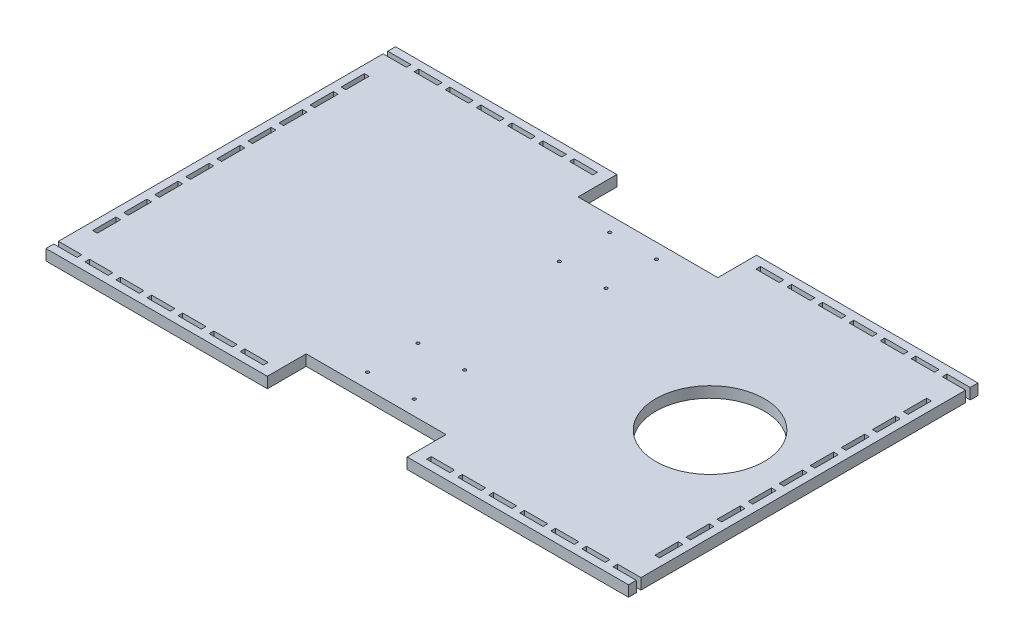
SolidWorks part; units mm, degrees
material "Thornel Mat VMA"
ref_plane "Front Plane" through (0, 0, 0) normal (0, 0, 1) x (1, 0, 0)
ref_plane "Top Plane" through (0, 0, 0) normal (0, 1, 0) x (1, 0, 0)
ref_plane "Right Plane" through (0, 0, 0) normal (1, 0, 0) x (0, 0, -1)
sketch "Sketch6" plane through (0, 0, 0) normal (0, 1, 0) x (1, 0, 0)
  line L0 (-187.5, 0) -> (187.5, 0) construction
  line L1 (-187.5, 112.5) -> (187.5, 112.5)
  line L2 (-187.5, 112.5) -> (-187.5, -112.5)
  line L3 (-187.5, -112.5) -> (187.5, -112.5)
  line L4 (187.5, 112.5) -> (187.5, -112.5)
  line L5 (0, -112.5) -> (0, -87.5) construction
  line L7 (187.5, -107.5) -> (172.5, -107.5)
  line L8 (187.5, -107.5) -> (187.5, -104.5)
  line L9 (187.5, -104.5) -> (172.5, -104.5)
  line L10 (172.5, -107.5) -> (172.5, -104.5)
  line L35 (187.5, 107.5) -> (172.5, 107.5)
  line L36 (187.5, 107.5) -> (187.5, 104.5)
  line L37 (187.5, 104.5) -> (172.5, 104.5)
  line L38 (172.5, 107.5) -> (172.5, 104.5)
  line L63 (-187.5, 104.5) -> (-172.5, 104.5)
  line L64 (-187.5, 104.5) -> (-187.5, 107.5)
  line L65 (-187.5, 107.5) -> (-172.5, 107.5)
  line L66 (-172.5, 104.5) -> (-172.5, 107.5)
  line L91 (-187.5, -107.5) -> (-172.5, -107.5)
  line L92 (-187.5, -107.5) -> (-187.5, -104.5)
  line L93 (-187.5, -104.5) -> (-172.5, -104.5)
  line L94 (-172.5, -107.5) -> (-172.5, -104.5)
  line L118 (167.5, 107.5) -> (152.5, 107.5)
  line L119 (152.5, 107.5) -> (152.5, 104.5)
  line L120 (167.5, 104.5) -> (152.5, 104.5)
  line L121 (167.5, 107.5) -> (167.5, 104.5)
  line L122 (167.5, -107.5) -> (152.5, -107.5)
  line L123 (152.5, -107.5) -> (152.5, -104.5)
  line L124 (167.5, -104.5) -> (152.5, -104.5)
  line L125 (167.5, -107.5) -> (167.5, -104.5)
  line L126 (147.5, 107.5) -> (132.5, 107.5)
  line L127 (132.5, 107.5) -> (132.5, 104.5)
  line L128 (147.5, 104.5) -> (132.5, 104.5)
  line L129 (147.5, 107.5) -> (147.5, 104.5)
  line L130 (147.5, -107.5) -> (132.5, -107.5)
  line L131 (132.5, -107.5) -> (132.5, -104.5)
  line L132 (147.5, -104.5) -> (132.5, -104.5)
  line L133 (147.5, -107.5) -> (147.5, -104.5)
  line L134 (127.5, 107.5) -> (112.5, 107.5)
  line L135 (112.5, 107.5) -> (112.5, 104.5)
  line L136 (127.5, 104.5) -> (112.5, 104.5)
  line L137 (127.5, 107.5) -> (127.5, 104.5)
  line L138 (127.5, -107.5) -> (112.5, -107.5)
  line L139 (112.5, -107.5) -> (112.5, -104.5)
  line L140 (127.5, -104.5) -> (112.5, -104.5)
  line L141 (127.5, -107.5) -> (127.5, -104.5)
  line L142 (107.5, 107.5) -> (92.5, 107.5)
  line L143 (92.5, 107.5) -> (92.5, 104.5)
  line L144 (107.5, 104.5) -> (92.5, 104.5)
  line L145 (107.5, 107.5) -> (107.5, 104.5)
  line L146 (107.5, -107.5) -> (92.5, -107.5)
  line L147 (92.5, -107.5) -> (92.5, -104.5)
  line L148 (107.5, -104.5) -> (92.5, -104.5)
  line L149 (107.5, -107.5) -> (107.5, -104.5)
  line L150 (87.5, 107.5) -> (72.5, 107.5)
  line L151 (72.5, 107.5) -> (72.5, 104.5)
  line L152 (87.5, 104.5) -> (72.5, 104.5)
  line L153 (87.5, 107.5) -> (87.5, 104.5)
  line L154 (87.5, -107.5) -> (72.5, -107.5)
  line L155 (72.5, -107.5) -> (72.5, -104.5)
  line L156 (87.5, -104.5) -> (72.5, -104.5)
  line L157 (87.5, -107.5) -> (87.5, -104.5)
  line L158 (67.5, 107.5) -> (52.5, 107.5)
  line L159 (52.5, 107.5) -> (52.5, 104.5)
  line L160 (67.5, 104.5) -> (52.5, 104.5)
  line L161 (67.5, 107.5) -> (67.5, 104.5)
  line L162 (67.5, -107.5) -> (52.5, -107.5)
  line L163 (52.5, -107.5) -> (52.5, -104.5)
  line L164 (67.5, -104.5) -> (52.5, -104.5)
  line L165 (67.5, -107.5) -> (67.5, -104.5)
  line L166 (-167.5, -107.5) -> (-152.5, -107.5)
  line L167 (-152.5, -107.5) -> (-152.5, -104.5)
  line L168 (-167.5, -104.5) -> (-152.5, -104.5)
  line L169 (-167.5, -107.5) -> (-167.5, -104.5)
  line L170 (-167.5, 104.5) -> (-152.5, 104.5)
  line L171 (-152.5, 104.5) -> (-152.5, 107.5)
  line L172 (-167.5, 107.5) -> (-152.5, 107.5)
  line L173 (-167.5, 104.5) -> (-167.5, 107.5)
  line L174 (-147.5, -107.5) -> (-132.5, -107.5)
  line L175 (-132.5, -107.5) -> (-132.5, -104.5)
  line L176 (-147.5, -104.5) -> (-132.5, -104.5)
  line L177 (-147.5, -107.5) -> (-147.5, -104.5)
  line L178 (-147.5, 104.5) -> (-132.5, 104.5)
  line L179 (-132.5, 104.5) -> (-132.5, 107.5)
  line L180 (-147.5, 107.5) -> (-132.5, 107.5)
  line L181 (-147.5, 104.5) -> (-147.5, 107.5)
  line L182 (-127.5, -107.5) -> (-112.5, -107.5)
  line L183 (-112.5, -107.5) -> (-112.5, -104.5)
  line L184 (-127.5, -104.5) -> (-112.5, -104.5)
  line L185 (-127.5, -107.5) -> (-127.5, -104.5)
  line L186 (-127.5, 104.5) -> (-112.5, 104.5)
  line L187 (-112.5, 104.5) -> (-112.5, 107.5)
  line L188 (-127.5, 107.5) -> (-112.5, 107.5)
  line L189 (-127.5, 104.5) -> (-127.5, 107.5)
  line L190 (-107.5, -107.5) -> (-92.5, -107.5)
  line L191 (-92.5, -107.5) -> (-92.5, -104.5)
  line L192 (-107.5, -104.5) -> (-92.5, -104.5)
  line L193 (-107.5, -107.5) -> (-107.5, -104.5)
  line L194 (-107.5, 104.5) -> (-92.5, 104.5)
  line L195 (-92.5, 104.5) -> (-92.5, 107.5)
  line L196 (-107.5, 107.5) -> (-92.5, 107.5)
  line L197 (-107.5, 104.5) -> (-107.5, 107.5)
  line L198 (-87.5, -107.5) -> (-72.5, -107.5)
  line L199 (-72.5, -107.5) -> (-72.5, -104.5)
  line L200 (-87.5, -104.5) -> (-72.5, -104.5)
  line L201 (-87.5, -107.5) -> (-87.5, -104.5)
  line L202 (-87.5, 104.5) -> (-72.5, 104.5)
  line L203 (-72.5, 104.5) -> (-72.5, 107.5)
  line L204 (-87.5, 107.5) -> (-72.5, 107.5)
  line L205 (-87.5, 104.5) -> (-87.5, 107.5)
  line L206 (-67.5, -107.5) -> (-52.5, -107.5)
  line L207 (-52.5, -107.5) -> (-52.5, -104.5)
  line L208 (-67.5, -104.5) -> (-52.5, -104.5)
  line L209 (-67.5, -107.5) -> (-67.5, -104.5)
  line L210 (-67.5, 104.5) -> (-52.5, 104.5)
  line L211 (-52.5, 104.5) -> (-52.5, 107.5)
  line L212 (-67.5, 107.5) -> (-52.5, 107.5)
  line L213 (-67.5, 104.5) -> (-67.5, 107.5)
  line L214 (0, -112.5) -> (0, -87.5) construction
  line L215 (45, -112.5) -> (-45, -112.5)
  line L216 (45, -112.5) -> (45, -87.5)
  line L217 (45, -87.5) -> (-45, -87.5)
  line L218 (-45, -112.5) -> (-45, -87.5)
  line L219 (45, 87.5) -> (-45, 87.5)
  line L220 (45, -100) -> (-45, -100) construction
  line L221 (-45, 112.5) -> (-45, 87.5)
  line L222 (45, 112.5) -> (-45, 112.5)
  line L223 (45, 112.5) -> (45, 87.5)
  line L224 (179.5, 0) -> (182.5, 0) construction
  line L225 (182.5, -7.5) -> (179.5, -7.5)
  line L226 (182.5, -7.5) -> (182.5, 7.5)
  line L227 (182.5, 7.5) -> (179.5, 7.5)
  line L228 (179.5, -7.5) -> (179.5, 7.5)
  line L229 (187.5, 0) -> (182.5, 0) construction
  line L230 (181, -7.5) -> (181, 7.5) construction
  line L231 (182.5, 12.5) -> (182.5, 27.5)
  line L232 (182.5, 12.5) -> (179.5, 12.5)
  line L233 (179.5, 12.5) -> (179.5, 27.5)
  line L234 (182.5, 27.5) -> (179.5, 27.5)
  line L235 (182.5, 32.5) -> (182.5, 47.5)
  line L236 (182.5, 32.5) -> (179.5, 32.5)
  line L237 (179.5, 32.5) -> (179.5, 47.5)
  line L238 (182.5, 47.5) -> (179.5, 47.5)
  line L239 (182.5, 52.5) -> (182.5, 67.5)
  line L240 (182.5, 52.5) -> (179.5, 52.5)
  line L241 (179.5, 52.5) -> (179.5, 67.5)
  line L242 (182.5, 67.5) -> (179.5, 67.5)
  line L243 (182.5, 72.5) -> (182.5, 87.5)
  line L244 (182.5, 72.5) -> (179.5, 72.5)
  line L245 (179.5, 72.5) -> (179.5, 87.5)
  line L246 (182.5, 87.5) -> (179.5, 87.5)
  line L247 (182.5, -7.5) -> (182.5, 7.5)
  line L248 (182.5, -7.5) -> (179.5, -7.5)
  line L249 (179.5, -7.5) -> (179.5, 7.5)
  line L250 (182.5, 7.5) -> (179.5, 7.5)
  line L251 (182.5, 12.5) -> (182.5, 27.5)
  line L252 (182.5, 12.5) -> (179.5, 12.5)
  line L253 (179.5, 12.5) -> (179.5, 27.5)
  line L254 (182.5, 27.5) -> (179.5, 27.5)
  line L255 (182.5, 32.5) -> (182.5, 47.5)
  line L256 (182.5, 32.5) -> (179.5, 32.5)
  line L257 (179.5, 32.5) -> (179.5, 47.5)
  line L258 (182.5, 47.5) -> (179.5, 47.5)
  line L259 (182.5, 52.5) -> (182.5, 67.5)
  line L260 (182.5, 52.5) -> (179.5, 52.5)
  line L261 (179.5, 52.5) -> (179.5, 67.5)
  line L262 (182.5, 67.5) -> (179.5, 67.5)
  line L263 (182.5, -27.5) -> (182.5, -12.5)
  line L264 (182.5, -27.5) -> (179.5, -27.5)
  line L265 (179.5, -27.5) -> (179.5, -12.5)
  line L266 (182.5, -12.5) -> (179.5, -12.5)
  line L267 (182.5, -7.5) -> (182.5, 7.5)
  line L268 (182.5, -7.5) -> (179.5, -7.5)
  line L269 (179.5, -7.5) -> (179.5, 7.5)
  line L270 (182.5, 7.5) -> (179.5, 7.5)
  line L271 (182.5, 12.5) -> (182.5, 27.5)
  line L272 (182.5, 12.5) -> (179.5, 12.5)
  line L273 (179.5, 12.5) -> (179.5, 27.5)
  line L274 (182.5, 27.5) -> (179.5, 27.5)
  line L275 (182.5, 32.5) -> (182.5, 47.5)
  line L276 (182.5, 32.5) -> (179.5, 32.5)
  line L277 (179.5, 32.5) -> (179.5, 47.5)
  line L278 (182.5, 47.5) -> (179.5, 47.5)
  line L279 (182.5, -47.5) -> (182.5, -32.5)
  line L280 (182.5, -47.5) -> (179.5, -47.5)
  line L281 (179.5, -47.5) -> (179.5, -32.5)
  line L282 (182.5, -32.5) -> (179.5, -32.5)
  line L283 (182.5, -27.5) -> (182.5, -12.5)
  line L284 (182.5, -27.5) -> (179.5, -27.5)
  line L285 (179.5, -27.5) -> (179.5, -12.5)
  line L286 (182.5, -12.5) -> (179.5, -12.5)
  line L287 (182.5, -7.5) -> (182.5, 7.5)
  line L288 (182.5, -7.5) -> (179.5, -7.5)
  line L289 (179.5, -7.5) -> (179.5, 7.5)
  line L290 (182.5, 7.5) -> (179.5, 7.5)
  line L291 (182.5, 12.5) -> (182.5, 27.5)
  line L292 (182.5, 12.5) -> (179.5, 12.5)
  line L293 (179.5, 12.5) -> (179.5, 27.5)
  line L294 (182.5, 27.5) -> (179.5, 27.5)
  line L295 (182.5, -67.5) -> (182.5, -52.5)
  line L296 (182.5, -67.5) -> (179.5, -67.5)
  line L297 (179.5, -67.5) -> (179.5, -52.5)
  line L298 (182.5, -52.5) -> (179.5, -52.5)
  line L299 (182.5, -47.5) -> (182.5, -32.5)
  line L300 (182.5, -47.5) -> (179.5, -47.5)
  line L301 (179.5, -47.5) -> (179.5, -32.5)
  line L302 (182.5, -32.5) -> (179.5, -32.5)
  line L303 (182.5, -27.5) -> (182.5, -12.5)
  line L304 (182.5, -27.5) -> (179.5, -27.5)
  line L305 (179.5, -27.5) -> (179.5, -12.5)
  line L306 (182.5, -12.5) -> (179.5, -12.5)
  line L307 (182.5, -7.5) -> (182.5, 7.5)
  line L308 (182.5, -7.5) -> (179.5, -7.5)
  line L309 (179.5, -7.5) -> (179.5, 7.5)
  line L310 (182.5, 7.5) -> (179.5, 7.5)
  line L311 (182.5, -27.5) -> (182.5, -12.5)
  line L312 (182.5, -27.5) -> (179.5, -27.5)
  line L313 (179.5, -27.5) -> (179.5, -12.5)
  line L314 (182.5, -12.5) -> (179.5, -12.5)
  line L315 (182.5, -47.5) -> (182.5, -32.5)
  line L316 (182.5, -47.5) -> (179.5, -47.5)
  line L317 (179.5, -47.5) -> (179.5, -32.5)
  line L318 (182.5, -32.5) -> (179.5, -32.5)
  line L319 (182.5, -67.5) -> (182.5, -52.5)
  line L320 (182.5, -67.5) -> (179.5, -67.5)
  line L321 (179.5, -67.5) -> (179.5, -52.5)
  line L322 (182.5, -52.5) -> (179.5, -52.5)
  line L323 (182.5, -87.5) -> (182.5, -72.5)
  line L324 (182.5, -87.5) -> (179.5, -87.5)
  line L325 (179.5, -87.5) -> (179.5, -72.5)
  line L326 (182.5, -72.5) -> (179.5, -72.5)
  line L327 (-179.5, 0) -> (-182.5, 0) construction
  line L328 (-179.5, 7.5) -> (-182.5, 7.5)
  line L329 (-179.5, 7.5) -> (-179.5, -7.5)
  line L330 (-179.5, -7.5) -> (-182.5, -7.5)
  line L331 (-182.5, 7.5) -> (-182.5, -7.5)
  line L332 (-187.5, 0) -> (-182.5, 0) construction
  line L333 (-181, 7.5) -> (-181, -7.5) construction
  line L334 (-179.5, 27.5) -> (-179.5, 12.5)
  line L335 (-179.5, 27.5) -> (-182.5, 27.5)
  line L336 (-182.5, 27.5) -> (-182.5, 12.5)
  line L337 (-179.5, 12.5) -> (-182.5, 12.5)
  line L338 (-179.5, 47.5) -> (-179.5, 32.5)
  line L339 (-179.5, 47.5) -> (-182.5, 47.5)
  line L340 (-182.5, 47.5) -> (-182.5, 32.5)
  line L341 (-179.5, 32.5) -> (-182.5, 32.5)
  line L342 (-179.5, 67.5) -> (-179.5, 52.5)
  line L343 (-179.5, 67.5) -> (-182.5, 67.5)
  line L344 (-182.5, 67.5) -> (-182.5, 52.5)
  line L345 (-179.5, 52.5) -> (-182.5, 52.5)
  line L346 (-179.5, 87.5) -> (-179.5, 72.5)
  line L347 (-179.5, 87.5) -> (-182.5, 87.5)
  line L348 (-182.5, 87.5) -> (-182.5, 72.5)
  line L349 (-179.5, 72.5) -> (-182.5, 72.5)
  line L350 (-179.5, 7.5) -> (-179.5, -7.5)
  line L351 (-179.5, 7.5) -> (-182.5, 7.5)
  line L352 (-182.5, 7.5) -> (-182.5, -7.5)
  line L353 (-179.5, -7.5) -> (-182.5, -7.5)
  line L354 (-179.5, 27.5) -> (-179.5, 12.5)
  line L355 (-179.5, 27.5) -> (-182.5, 27.5)
  line L356 (-182.5, 27.5) -> (-182.5, 12.5)
  line L357 (-179.5, 12.5) -> (-182.5, 12.5)
  line L358 (-179.5, 47.5) -> (-179.5, 32.5)
  line L359 (-179.5, 47.5) -> (-182.5, 47.5)
  line L360 (-182.5, 47.5) -> (-182.5, 32.5)
  line L361 (-179.5, 32.5) -> (-182.5, 32.5)
  line L362 (-179.5, 67.5) -> (-179.5, 52.5)
  line L363 (-179.5, 67.5) -> (-182.5, 67.5)
  line L364 (-182.5, 67.5) -> (-182.5, 52.5)
  line L365 (-179.5, 52.5) -> (-182.5, 52.5)
  line L366 (-179.5, -12.5) -> (-179.5, -27.5)
  line L367 (-179.5, -12.5) -> (-182.5, -12.5)
  line L368 (-182.5, -12.5) -> (-182.5, -27.5)
  line L369 (-179.5, -27.5) -> (-182.5, -27.5)
  line L370 (-179.5, 7.5) -> (-179.5, -7.5)
  line L371 (-179.5, 7.5) -> (-182.5, 7.5)
  line L372 (-182.5, 7.5) -> (-182.5, -7.5)
  line L373 (-179.5, -7.5) -> (-182.5, -7.5)
  line L374 (-179.5, 27.5) -> (-179.5, 12.5)
  line L375 (-179.5, 27.5) -> (-182.5, 27.5)
  line L376 (-182.5, 27.5) -> (-182.5, 12.5)
  line L377 (-179.5, 12.5) -> (-182.5, 12.5)
  line L378 (-179.5, 47.5) -> (-179.5, 32.5)
  line L379 (-179.5, 47.5) -> (-182.5, 47.5)
  line L380 (-182.5, 47.5) -> (-182.5, 32.5)
  line L381 (-179.5, 32.5) -> (-182.5, 32.5)
  line L382 (-179.5, -32.5) -> (-179.5, -47.5)
  line L383 (-179.5, -32.5) -> (-182.5, -32.5)
  line L384 (-182.5, -32.5) -> (-182.5, -47.5)
  line L385 (-179.5, -47.5) -> (-182.5, -47.5)
  line L386 (-179.5, -12.5) -> (-179.5, -27.5)
  line L387 (-179.5, -12.5) -> (-182.5, -12.5)
  line L388 (-182.5, -12.5) -> (-182.5, -27.5)
  line L389 (-179.5, -27.5) -> (-182.5, -27.5)
  line L390 (-179.5, 7.5) -> (-179.5, -7.5)
  line L391 (-179.5, 7.5) -> (-182.5, 7.5)
  line L392 (-182.5, 7.5) -> (-182.5, -7.5)
  line L393 (-179.5, -7.5) -> (-182.5, -7.5)
  line L394 (-179.5, 27.5) -> (-179.5, 12.5)
  line L395 (-179.5, 27.5) -> (-182.5, 27.5)
  line L396 (-182.5, 27.5) -> (-182.5, 12.5)
  line L397 (-179.5, 12.5) -> (-182.5, 12.5)
  line L398 (-179.5, -52.5) -> (-179.5, -67.5)
  line L399 (-179.5, -52.5) -> (-182.5, -52.5)
  line L400 (-182.5, -52.5) -> (-182.5, -67.5)
  line L401 (-179.5, -67.5) -> (-182.5, -67.5)
  line L402 (-179.5, -32.5) -> (-179.5, -47.5)
  line L403 (-179.5, -32.5) -> (-182.5, -32.5)
  line L404 (-182.5, -32.5) -> (-182.5, -47.5)
  line L405 (-179.5, -47.5) -> (-182.5, -47.5)
  line L406 (-179.5, -12.5) -> (-179.5, -27.5)
  line L407 (-179.5, -12.5) -> (-182.5, -12.5)
  line L408 (-182.5, -12.5) -> (-182.5, -27.5)
  line L409 (-179.5, -27.5) -> (-182.5, -27.5)
  line L410 (-179.5, 7.5) -> (-179.5, -7.5)
  line L411 (-179.5, 7.5) -> (-182.5, 7.5)
  line L412 (-182.5, 7.5) -> (-182.5, -7.5)
  line L413 (-179.5, -7.5) -> (-182.5, -7.5)
  line L414 (-179.5, -12.5) -> (-179.5, -27.5)
  line L415 (-179.5, -12.5) -> (-182.5, -12.5)
  line L416 (-182.5, -12.5) -> (-182.5, -27.5)
  line L417 (-179.5, -27.5) -> (-182.5, -27.5)
  line L418 (-179.5, -32.5) -> (-179.5, -47.5)
  line L419 (-179.5, -32.5) -> (-182.5, -32.5)
  line L420 (-182.5, -32.5) -> (-182.5, -47.5)
  line L421 (-179.5, -47.5) -> (-182.5, -47.5)
  line L422 (-179.5, -52.5) -> (-179.5, -67.5)
  line L423 (-179.5, -52.5) -> (-182.5, -52.5)
  line L424 (-182.5, -52.5) -> (-182.5, -67.5)
  line L425 (-179.5, -67.5) -> (-182.5, -67.5)
  line L426 (-179.5, -72.5) -> (-179.5, -87.5)
  line L427 (-179.5, -72.5) -> (-182.5, -72.5)
  line L428 (-182.5, -72.5) -> (-182.5, -87.5)
  line L429 (-179.5, -87.5) -> (-182.5, -87.5)
  line L430 (0, 0) -> (0, 112.5) construction
  line L432 (-15, -45.52) -> (15, -45.52) construction
  line L433 (45, 87.5) -> (45, 61.72) construction
  line L434 (45, 61.72) -> (15, 61.72) construction
  line L435 (15, -45.52) -> (15, -77.92) construction
  line L439 (15, -61.72) -> (45, -87.5) construction
  line L440 (45, -87.5) -> (45, -61.72) construction
  line L441 (45, -61.72) -> (15, -61.72) construction
  line L444 (-15, -45.52) -> (-16, -45.52) construction
  line L445 (15, 61.72) -> (15, 45.52) construction
  line L446 (15, 45.52) -> (-15, 45.52) construction
  line L448 (-15, -45.52) -> (-15, -77.92) construction
  line L449 (-15, -77.92) -> (-16, -77.92) construction
  line L450 (15, 77.92) -> (-15, 77.92) construction
  line L451 (-15, 77.92) -> (-15, 45.52) construction
  line L452 (-15, -77.92) -> (15, -77.92) construction
  line L453 (15, 77.92) -> (15, 61.72) construction
  line L454 (15, 61.72) -> (45, 87.5) construction
  circle A0 centre (127.5, 0) radius 35
  circle A1 centre (15, -45.52) radius 1
  circle A2 centre (-15, -45.52) radius 1
  circle A3 centre (-15, -77.92) radius 1
  circle A4 centre (15, -77.92) radius 1
  circle A5 centre (-15, 45.52) radius 1
  circle A6 centre (-15, 77.92) radius 1
  circle A7 centre (15, 77.92) radius 1
  circle A8 centre (15, 45.52) radius 1
  circle A10 centre (-172, 0) radius 1.5 construction
  point P8 (0, 0)
  dimension "D3" = 70
  dimension "D38" = 2
  dimension "D43" = 3
  dimension "D1" = 375
  dimension "D2" = 225
  dimension "D4" = 15
  dimension "D5" = 5
  dimension "D6" = 3
  dimension "D7" = 3
  dimension "D8" = 5
  dimension "D9" = 15
  dimension "D10" = 3
  dimension "D11" = 15
  dimension "D12" = 5
  dimension "D13" = 3
  dimension "D14" = 15
  dimension "D15" = 5
  dimension "D16" = 60
  dimension "D19" = 5
  dimension "D20" = 5
  dimension "D21" = 90
  dimension "D22" = 25
  dimension "D23" = 3
  dimension "D24" = 15
  dimension "D25" = 5
  dimension "D28" = 5
  dimension "D29" = 5
  dimension "D30" = 3
  dimension "D31" = 15
  dimension "D32" = 5
  dimension "D35" = 5
  dimension "D36" = 5
  dimension "D37" = 25.78
  dimension "D39" = 32.4
  dimension "D40" = 30
  dimension "D41" = 30
  dimension "D42" = 16.2
  dimension "D44" = 7.5
  dimension "D17" = 7
  dimension "D18" = 7
  dimension "D26" = 5
  dimension "D27" = 5
  dimension "D33" = 5
  dimension "D34" = 5
extrude "Boss-Extrude3" add sketch "Sketch6" along normal blind 7
